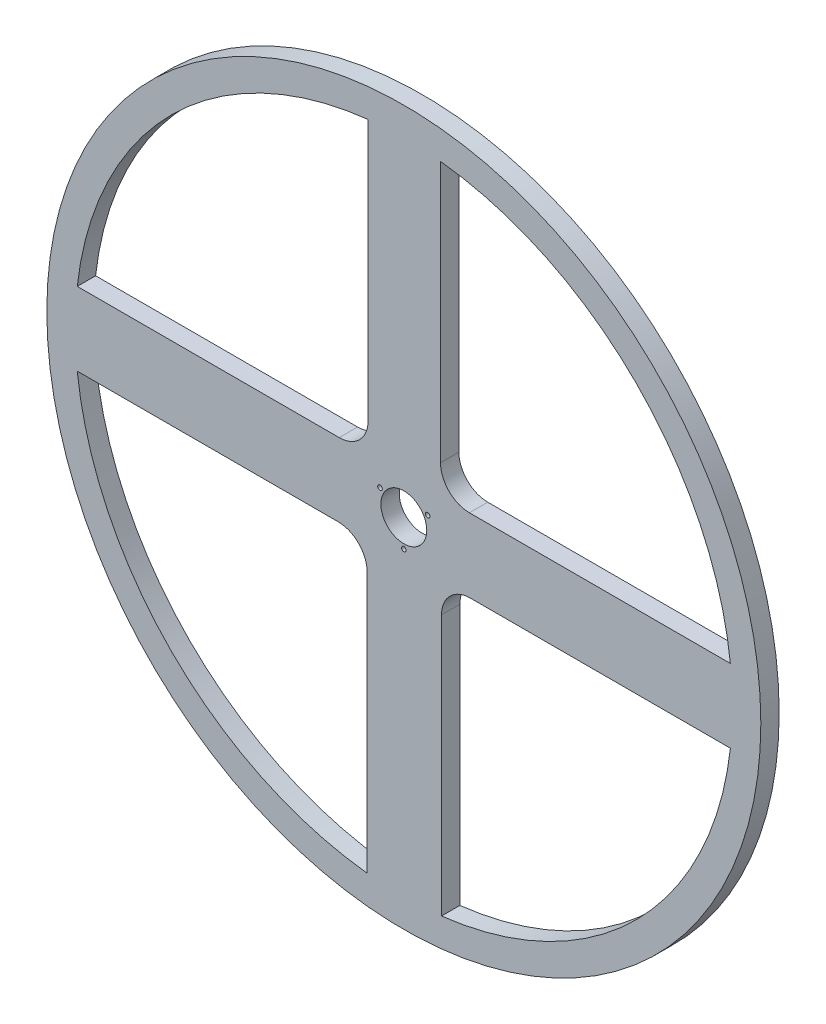
SolidWorks part; units mm, degrees
ref_plane "Front Plane" through (0, 0, 0) normal (0, 0, 1) x (1, 0, 0)
ref_plane "Top Plane" through (0, 0, 0) normal (0, 1, 0) x (1, 0, 0)
ref_plane "Right Plane" through (0, 0, 0) normal (1, 0, 0) x (0, 0, -1)
sketch "Sketch1" plane through (0, 0, 0) normal (0, 0, 1) x (1, 0, 0)
  line L0 (0, -113.71) -> (0, 113.71) construction
  line L2 (12.7, 22.7) -> (12.7, 116.188)
  line L4 (-12.3556, 22.7) -> (-12.3556, 113.0367)
  line L5 (13.0444, -119.3392) -> (-12.3556, 113.0367) construction
  line L6 (12.7, 116.188) -> (-12.7, -116.188) construction
  line L7 (-116.188, -12.7) -> (-22.7, -12.7)
  line L9 (-116.188, 12.7) -> (-22.3556, 12.7)
  line L11 (-116.188, -12.7) -> (116.188, 12.7) construction
  line L12 (-116.188, 12.7) -> (116.188, -12.7) construction
  line L13 (-113.71, 0) -> (113.71, 0) construction
  line L14 (22.7, 12.7) -> (116.188, 12.7)
  line L15 (13.0444, -22.7) -> (13.0444, -119.3392)
  line L16 (-12.7, -22.7) -> (-12.7, -116.188)
  line L17 (23.0444, -12.7) -> (116.188, -12.7)
  circle A0 centre (0, 0) radius 123.5325
  circle A1 centre (0, 0) radius 113.71
  arc A2 (-12.3556, 22.7) -> (-22.3556, 12.7) centre (-22.3556, 22.7) cw
  arc A3 (22.7, 12.7) -> (12.7, 22.7) centre (22.7, 22.7) cw
  arc A4 (-12.7, -22.7) -> (-22.7, -12.7) centre (-22.7, -22.7) ccw
  arc A5 (13.0444, -22.7) -> (23.0444, -12.7) centre (23.0444, -22.7) cw
  point P28 (13.0444, -12.7)
  dimension "D1" = 247.065
  dimension "D2" = 227.42
  dimension "D5" = 10
  dimension "D6" = 10
  dimension "D7" = 10
  dimension "D8" = 10
  dimension "D3" = 12.7
  dimension "D4" = 12.7
extrude "Boss-Extrude1" add sketch "Sketch1" along normal blind 6.35 contours A0 A1 | L15 A5 L17 A1 L14 A3 L2 L4 A2 L9 L7 A4 L16
sketch "Sketch2" plane through (0, 0, 6.35) normal (0, 0, 1) x (1, 0, 0)
  circle A0 centre (0, 0) radius 7.9375
  dimension "D1" = 15.875
extrude "Cut-Extrude1" cut sketch "Sketch2" against normal up to next contours A0
sketch "Sketch3" plane through (0, 0, 6.35) normal (0, 0, 1) x (1, 0, 0)
  circle A0 centre (0, 0) radius 9.525
  circle A1 centre (0, -9.525) radius 0.7937
  circle A2 centre (8.2489, 4.7625) radius 0.7938
  circle A3 centre (-8.2489, 4.7625) radius 0.7937
  dimension "D1" = 19.05
  dimension "D2" = 120
  dimension "D3" = 120
extrude "Cut-Extrude2" cut sketch "Sketch3" against normal up to next contours A0 A3 | A0 A3 | A0 A2 | A0 A2 | A0 A1 | A0 A1
